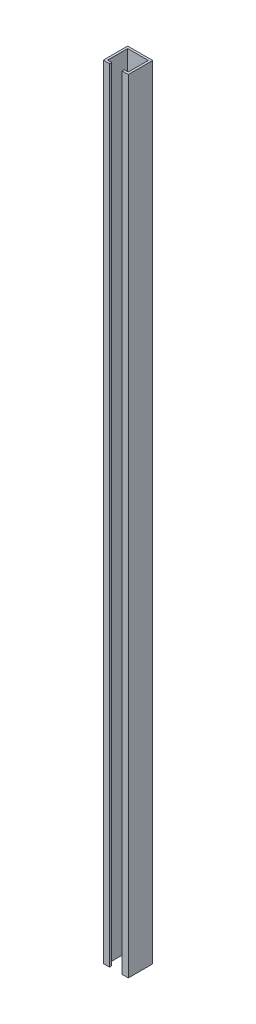
SolidWorks part; units mm, degrees
ref_plane "Front Plane" through (0, 0, 0) normal (0, 0, 1) x (1, 0, 0)
ref_plane "Top Plane" through (0, 0, 0) normal (0, 1, 0) x (1, 0, 0)
ref_plane "Right Plane" through (0, 0, 0) normal (1, 0, 0) x (0, 0, -1)
sketch "Sketch2" plane through (0, 0, 0) normal (0, 1, 0) x (1, 0, 0)
  line L0 (9.5, 2) -> (5.75, 2)
  line L1 (11.5, 22.4567) -> (-11.5, 22.4567)
  line L2 (-11.5, 22.4567) -> (-11.5, 0)
  line L3 (-11.5, 0) -> (-5.75, 0)
  line L4 (11.5, 0) -> (5.75, 0)
  line L5 (11.5, 22.4567) -> (11.5, 0)
  line L6 (9.5, 20.4567) -> (9.5, 2)
  line L7 (9.5, 20.4567) -> (-9.5, 20.4567)
  line L8 (-9.5, 20.4567) -> (-9.5, 2)
  line L9 (-9.5, 2) -> (-5.75, 2)
  line L10 (-5.75, 0) -> (-5.75, 2)
  line L11 (5.75, 0) -> (5.75, 2)
  dimension "D1" = 2
  dimension "D2" = 22.4567
  dimension "D3" = 5.75
extrude "Boss-Extrude1" add sketch "Sketch2" along normal mid plane 720
